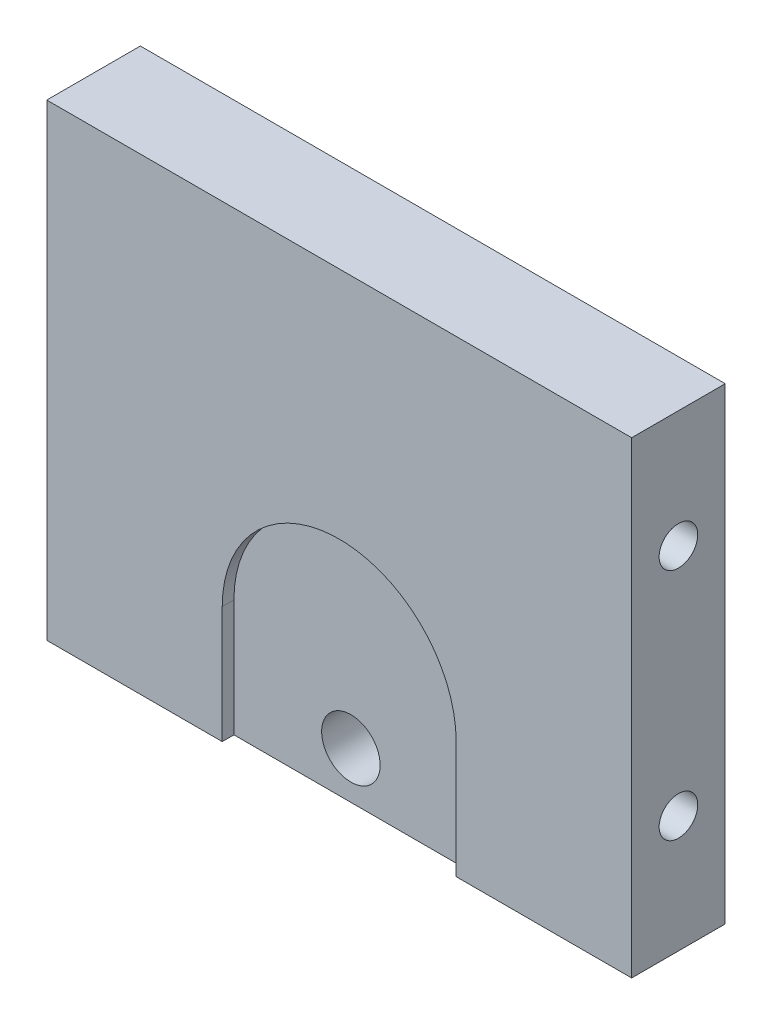
SolidWorks part; units mm, degrees
material "6061 Сплав"
ref_plane "Front" through (0, 0, 0) normal (0, 0, 1) x (1, 0, 0)
ref_plane "Top" through (0, 0, 0) normal (0, 1, 0) x (1, 0, 0)
ref_plane "Right" through (0, 0, 0) normal (1, 0, 0) x (0, 0, -1)
sketch "Эскиз1" plane through (0, 0, 0) normal (0, 0, 1) x (1, 0, 0)
  line L1 (-25, 20) -> (25, 20)
  line L2 (-25, 20) -> (-25, -20)
  line L3 (-25, -20) -> (25, -20)
  line L4 (25, 20) -> (25, -20)
  line L5 (-25, 20) -> (25, -20) construction
  line L6 (-25, -20) -> (25, 20) construction
  point P0 (0, 0)
  dimension "D1" = 50
  dimension "D2" = 40
extrude "Бобышка-Вытянуть1" add sketch "Эскиз1" along normal blind 8
sketch "Эскиз2" plane through (25, 0, 0) normal (1, 0, 0) x (0, 0, -1)
  line L0 (0, -20) -> (0, 20) construction
  line L1 (-8, -20) -> (0, -20) construction
  line L2 (-8, 20) -> (0, 20) construction
  circle A0 centre (-4, 10) radius 1.65
  circle A1 centre (-4, -10) radius 1.65
  dimension "D1" = 4
  dimension "D2" = 4
  dimension "D3" = 10
  dimension "D4" = 10
extrude "Вырез-Вытянуть1" cut sketch "Эскиз2" against normal blind 15
sketch "Эскиз3" plane through (0, 0, 8) normal (0, 0, 1) x (1, 0, 0)
  line L0 (-10, -20) -> (10, -20)
  line L1 (-25, -20) -> (25, -20) construction
  line L2 (10, -20) -> (10, -10)
  line L3 (-10, -20) -> (-10, -10)
  line L4 (-25, 20) -> (-25, -20) construction
  arc A0 (-10, -10) -> (10, -10) centre (0, -10) cw
  dimension "D1" = 20
  dimension "D2" = 15
  dimension "D3" = 10
extrude "Вырез-Вытянуть2" cut sketch "Эскиз3" against normal blind 1
sketch "Эскиз4" plane through (0, 0, 7) normal (0, 0, 1) x (1, 0, 0)
  line L0 (-10, -20) -> (10, -20) construction
  circle A0 centre (0, -16) radius 2.5
  point P2 (0, -20)
  dimension "D1" = 5
  dimension "D2" = 4
extrude "Вырез-Вытянуть3" cut sketch "Эскиз4" against normal blind 10
